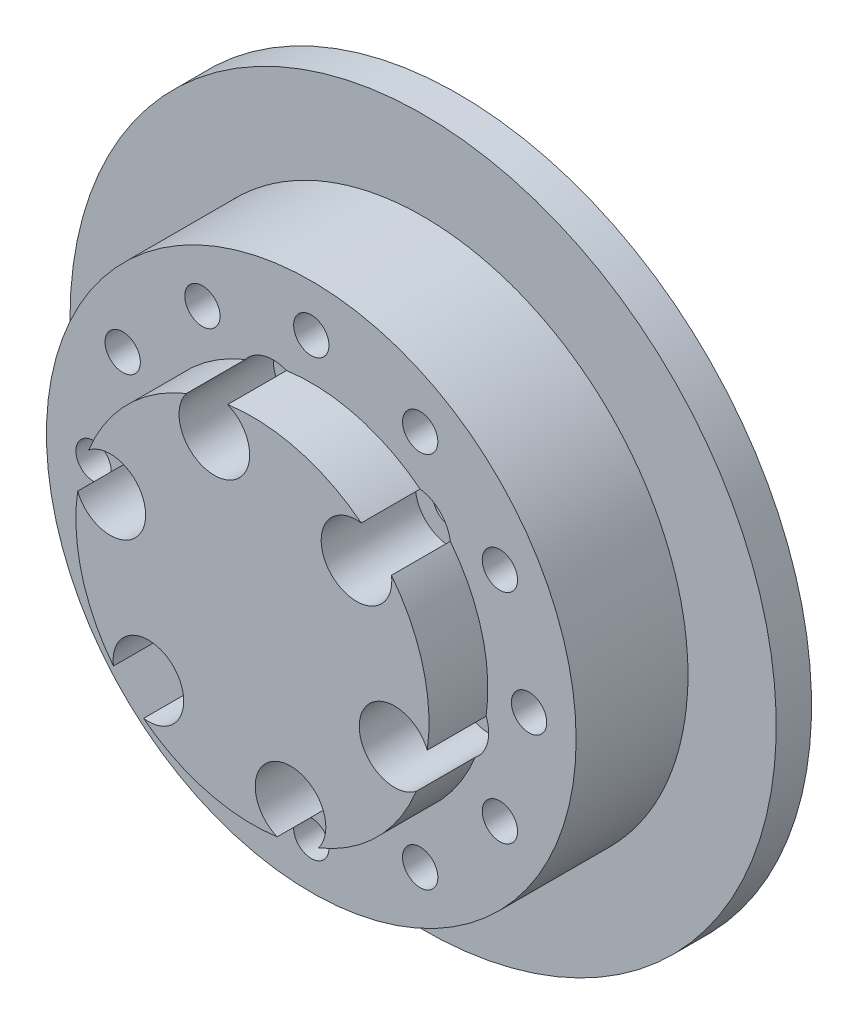
SolidWorks part; units mm, degrees
ref_plane "前视基准面" through (0, 0, 0) normal (0, 0, 1) x (1, 0, 0)
ref_plane "上视基准面" through (0, 0, 0) normal (0, 1, 0) x (1, 0, 0)
ref_plane "右视基准面" through (0, 0, 0) normal (1, 0, 0) x (0, 0, -1)
other "Configuration Table"
sketch "草图1" plane through (0, 0, 0) normal (0, 0, 1) x (1, 0, 0)
  circle A0 centre (0, 0) radius 22.5
  dimension "D1" = 45
extrude "凸台-拉伸1" add sketch "草图1" along normal blind 12.5
sketch "草图2" plane through (0, 0, 12.5) normal (0, 0, 1) x (1, 0, 0)
  circle A0 centre (0, 0) radius 15
  dimension "D1" = 30
extrude "凸台-拉伸2" add sketch "草图2" along normal blind 5
sketch "草图3" plane through (0, 0, 12.5) normal (0, 0, 1) x (1, 0, 0)
  circle A0 centre (0, 0) radius 18.5 construction
  circle A1 centre (0, 18.5) radius 1.5
  dimension "D1" = 37
  dimension "D2" = 3
extrude "切除-拉伸1" cut sketch "草图3" against normal blind 5
sketch "草图5" plane through (0, 0, 12.5) normal (0, 0, 1) x (1, 0, 0)
  circle A0 centre (0, 18.5) radius 1.5
  dimension "D1" = 3
extrude "切除-拉伸2" cut sketch "草图5" against normal through all
sketch "草图9" plane through (0, 0, 0) normal (0, 0, -1) x (-1, 0, 0)
  line L1 (1.2045, 21.4381) -> (-1.9422, 21.0122)
  line L2 (-1.9422, 21.0122) -> (-3.1467, 18.0741)
  line L3 (-3.1467, 18.0741) -> (-1.2045, 15.5619)
  line L4 (-1.2045, 15.5619) -> (1.9422, 15.9878)
  line L5 (1.9422, 15.9878) -> (3.1467, 18.9259)
  line L6 (3.1467, 18.9259) -> (1.2045, 21.4381)
  circle A0 centre (0, 18.5) radius 2.75 construction
  dimension "D1" = 5.5
extrude "切除-拉伸6" cut sketch "草图9" against normal blind 3
pattern_circular "阵列(圆周)1" count 12 over 360 about axis through (0, 0, 0) along (0, 0, 1) of "切除-拉伸1", "切除-拉伸6", "切除-拉伸2"
sketch "草图6" plane through (0, 0, 0) normal (0, 0, -1) x (-1, 0, 0)
  line L0 (0, 18.5) -> (9.25, 16.0215) construction
  line L1 (4.625, 17.2607) -> (0, 0) construction
  circle A0 centre (0, 0) radius 12.5 construction
  circle A1 centre (3.2352, 12.0741) radius 1.5
  dimension "D1" = 3
  dimension "D2" = 25
sketch "草图7" plane through (0, 0, 17.5) normal (0, 0, 1) x (1, 0, 0)
  circle A0 centre (-3.2352, 12.0741) radius 3
  dimension "D1" = 6
extrude "切除-拉伸3" cut sketch "草图6" against normal through all contours A1
extrude "切除-拉伸4" cut sketch "草图7" against normal offset from surface (8 mm away) 3 contours A0 up to face at (-15.2715, 10.549, 12.5) offset beyond the face yes
pattern_circular "阵列(圆周)2" count 6 over 360 about axis through (0, 0, 0) along (0, 0, 1) of "切除-拉伸3", "切除-拉伸4"
sketch "草图8" plane through (0, 0, 0) normal (0, 0, -1) x (-1, 0, 0)
  line L0 (0, 0) -> (-12940.9523, 48296.2913) construction
  line L1 (3.2352, 12.0741) -> (-8.8388, 8.8388) construction
  line L2 (-8.8388, 8.8388) -> (-12.0741, -3.2352) construction
  line L3 (-12.0741, -3.2352) -> (-3.2352, -12.0741) construction
  line L4 (-3.2352, -12.0741) -> (8.8388, -8.8388) construction
  line L5 (8.8388, -8.8388) -> (12.0741, 3.2352) construction
  line L6 (12.0741, 3.2352) -> (3.2352, 12.0741) construction
  circle A0 centre (0, 0) radius 10.8253 construction
  circle A1 centre (-2.64, 9.8524) radius 2
  circle A2 centre (0, 0) radius 10.2 construction
  point P13 (-2.8018, 10.4565)
  dimension "D1" = 4
  dimension "D2" = 20.4
extrude "切除-拉伸5" cut sketch "草图8" against normal blind 4
pattern_circular "阵列(圆周)3" count 6 every 60 about axis through (0, 0, 0) along (0, 0, 1) of "切除-拉伸5"
sketch "草图10" plane through (0, 0, 0) normal (0, 0, -1) x (-1, 0, 0)
  circle A0 centre (0, 0) radius 22.5
  circle A1 centre (0, 0) radius 30
  circle A2 centre (0, 0) radius 22.5 construction
  dimension "D1" = 60
extrude "凸台-拉伸3" add sketch "草图10" against normal blind 3 separate body
